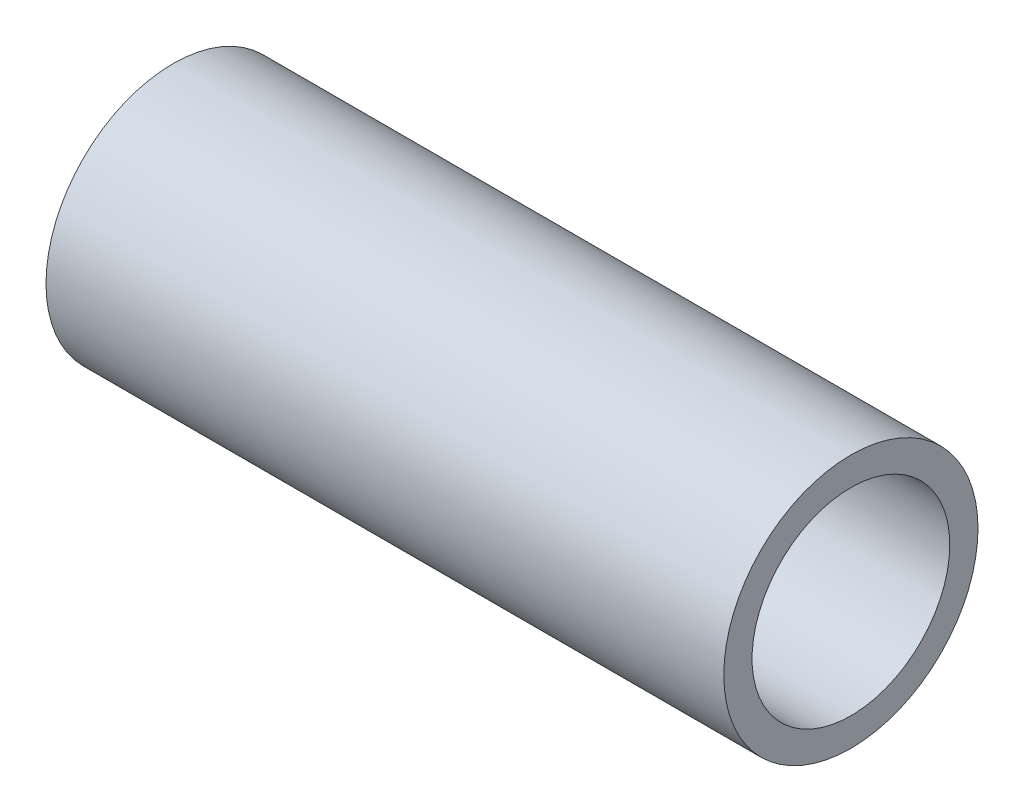
SolidWorks part; units mm, degrees
ref_plane "Front Plane" through (0, 0, 0) normal (0, 0, 1) x (1, 0, 0)
ref_plane "Top Plane" through (0, 0, 0) normal (0, 1, 0) x (1, 0, 0)
ref_plane "Right Plane" through (0, 0, 0) normal (1, 0, 0) x (0, 0, -1)
sketch "Sketch1" plane through (0, 0, 0) normal (1, 0, 0) x (0, 0, -1)
  circle A0 centre (0, 0) radius 9
  circle A1 centre (0, 0) radius 7
  dimension "D1" = 14
  dimension "D2" = 18
extrude "Boss-Extrude1" add sketch "Sketch1" along normal mid plane 48
